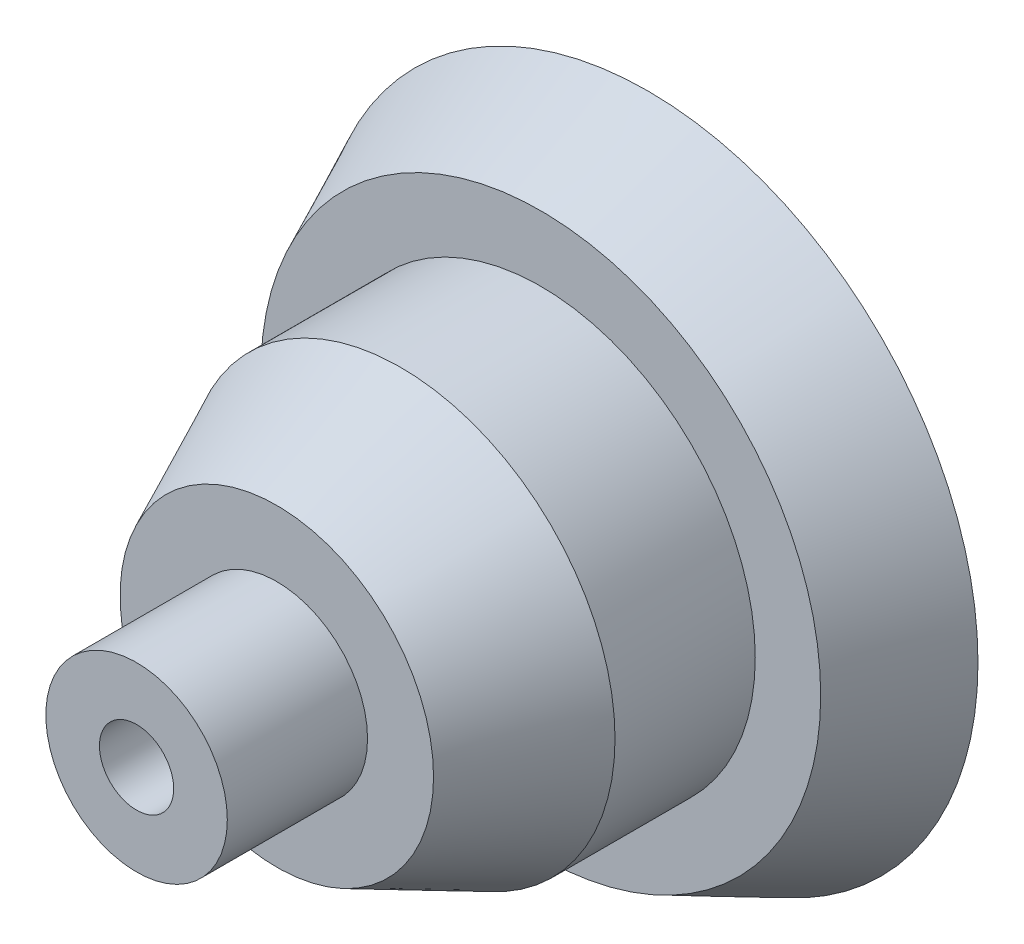
SolidWorks part; units mm, degrees
ref_plane "Front Plane" through (0, 0, 0) normal (0, 0, 1) x (1, 0, 0)
ref_plane "Top Plane" through (0, 0, 0) normal (0, 1, 0) x (1, 0, 0)
ref_plane "Right Plane" through (0, 0, 0) normal (1, 0, 0) x (0, 0, -1)
sketch "Sketch1" plane through (0, 0, 0) normal (1, 0, 0) x (0, 0, -1)
  line L1 (-38.5, 4.5) -> (-38.5, 11)
  line L2 (-38.5, 11) -> (-21.5, 11)
  line L3 (-21.5, 11) -> (-21.5, 19)
  line L4 (-21.5, 19) -> (-6.5, 26)
  line L5 (-6.5, 26) -> (10.5, 26)
  line L6 (10.5, 26) -> (10.5, 33.9325)
  line L7 (10.5, 33.9325) -> (23.5, 40)
  line L8 (23.5, 40) -> (23.5, 4.5)
  line L9 (23.5, 4.5) -> (16.5, 4.5)
  line L10 (16.5, 4.5) -> (16.5, 11)
  line L11 (16.5, 11) -> (-16.5, 11)
  line L12 (-16.5, 11) -> (-16.5, 4.5)
  line L14 (-38.5, 4.5) -> (-16.5, 4.5)
  line L15 (-50, 0) -> (50, 0) construction
  point P14 (0, 11)
  dimension "D1" = 40
  dimension "D2" = 62
  dimension "D3" = 45
  dimension "D4" = 4.5
  dimension "D5" = 30
  dimension "D6" = 13
  dimension "D7" = 11
  dimension "D8" = 7
  dimension "D9" = 40
  dimension "D10" = 26
  dimension "D11" = 19
  dimension "D12" = 115.02
  dimension "D13" = 100
revolve "Revolve1" add sketch "Sketch1" angle 360 about L15
